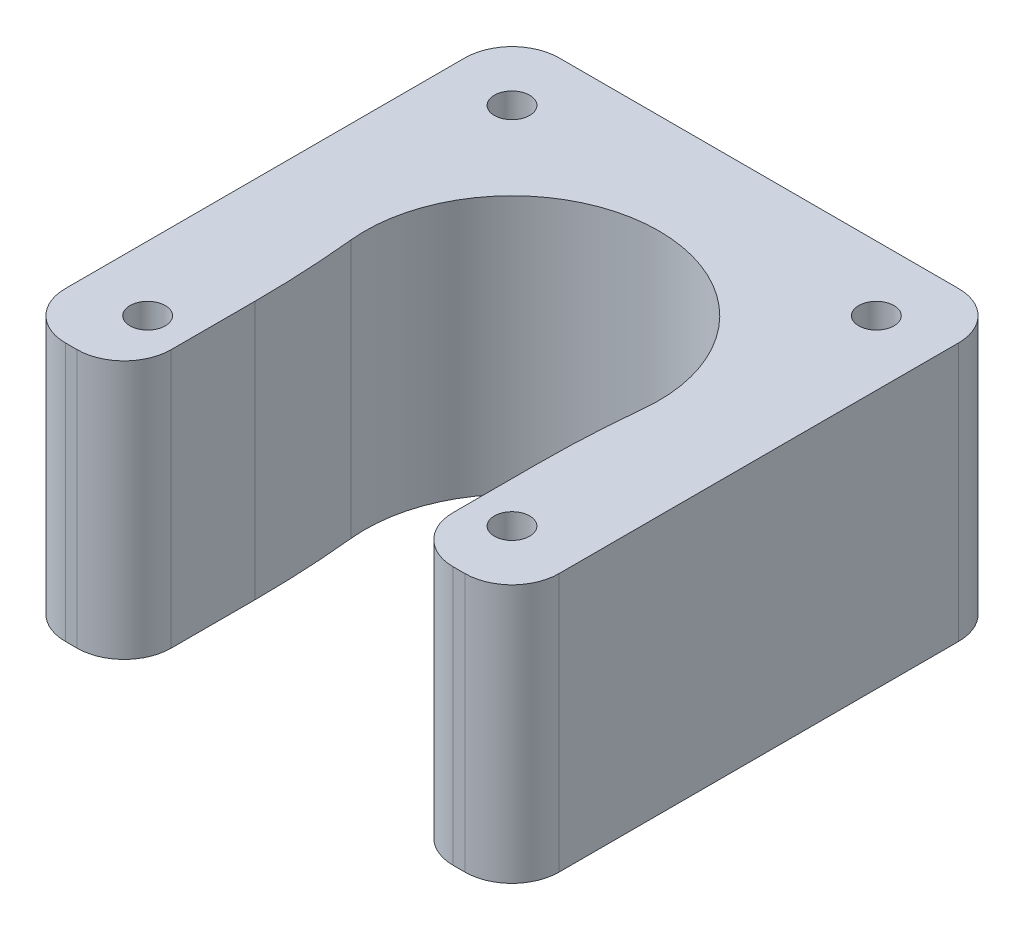
SolidWorks part; units mm, degrees
material "ABS PC"
ref_plane "Front Plane" through (0, 0, 0) normal (0, 0, 1) x (1, 0, 0)
ref_plane "Top Plane" through (0, 0, 0) normal (0, 1, 0) x (1, 0, 0)
ref_plane "Right Plane" through (0, 0, 0) normal (1, 0, 0) x (0, 0, -1)
sketch "Sketch1" plane through (0, 0, 0) normal (0, 1, 0) x (1, 0, 0)
  line L0 (0, -12.5) -> (0, -15.5)
  line L1 (-21, -21) -> (21, -21)
  line L2 (-21, -21) -> (-21, 21)
  line L3 (-21, 21) -> (21, 21)
  line L4 (21, -21) -> (21, 21)
  line L5 (-21, -21) -> (21, 21) construction
  line L6 (-21, 21) -> (21, -21) construction
  line L7 (-15.5, -15.5) -> (15.5, -15.5)
  line L8 (-15.5, -15.5) -> (-15.5, 15.5)
  line L9 (-15.5, 15.5) -> (15.5, 15.5)
  line L10 (15.5, -15.5) -> (15.5, 15.5)
  line L11 (-15.5, -15.5) -> (15.5, 15.5) construction
  line L12 (-15.5, 15.5) -> (15.5, -15.5) construction
  line L13 (15.5, -15.5) -> (12, -15.5)
  line L14 (12, -15.5) -> (12, -3.5)
  line L15 (-15.5, -15.5) -> (-12, -15.5)
  line L16 (-12, -15.5) -> (-12, -3.5)
  line L17 (-12, -15.5) -> (-12, -21)
  line L18 (12, -15.5) -> (12, -21)
  circle A0 centre (0, 0) radius 12.5
  circle A1 centre (-15.5, 15.5) radius 1.5
  circle A2 centre (15.5, 15.5) radius 1.5
  circle A3 centre (15.5, -15.5) radius 1.5
  circle A4 centre (-15.5, -15.5) radius 1.5
  point P0 (0, 0)
  dimension "D1" = 42
  dimension "D2" = 25
  dimension "D3" = 3
  dimension "D4" = 31
  dimension "D5" = 3.5
  dimension "D6" = 3.5
extrude "Boss-Extrude1" add sketch "Sketch1" along normal blind 22 contours A4 L8 A1 L9 A2 L10 A3 L7 L18 L1 L4 L3 L2 L17 L15 | A4 L15 L16 A0 L14 L7 A3 L10 A2 L9 A1 L8
fillet "Fillet1" radius 85 2 edges at (-12, 11, 3.5) (12, 11, 3.5)
fillet "Fillet2" radius 4 6 edges at (-21, 11, 21) (-12, 11, 21) (21, 11, 21) (12, 11, 21) (-21, 11, -21) (21, 11, -21)
